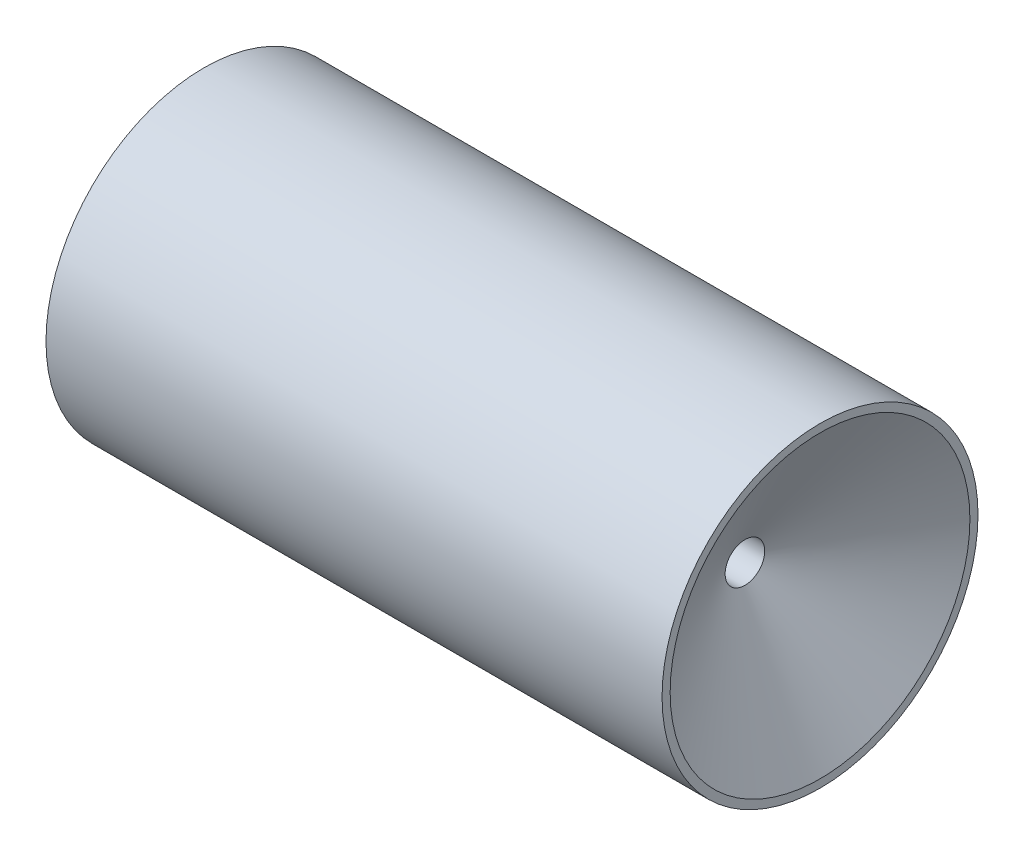
SolidWorks part; units mm, degrees
material "C (Graphite)"
ref_plane "Front Plane" through (0, 0, 0) normal (0, 0, 1) x (1, 0, 0)
ref_plane "Top Plane" through (0, 0, 0) normal (0, 1, 0) x (1, 0, 0)
ref_plane "Right Plane" through (0, 0, 0) normal (1, 0, 0) x (0, 0, -1)
sketch "Sketch1" plane through (0, 0, 0) normal (0, 0, 1) x (1, 0, 0)
  line L0 (11.2724, 0) -> (-90.9907, 0) construction
  line L7 (-78, 20) -> (0, 20)
  line L16 (-50.0357, 2.507) -> (-78, 10)
  line L17 (-78, 10) -> (-78, 20)
  line L18 (-9.5084, 2.507) -> (-50.0357, 2.507)
  line L19 (0, 20) -> (0, 18.9761)
  line L20 (0, 18.9761) -> (-9.5084, 2.507)
  point P7 (-78, 9.7251)
  dimension "D2" = 60
  dimension "D3" = 78
  dimension "D1" = 40
  dimension "D4" = 15
  dimension "D5" = 10
revolve "Revolve1" add sketch "Sketch1" angle 360 about L0
